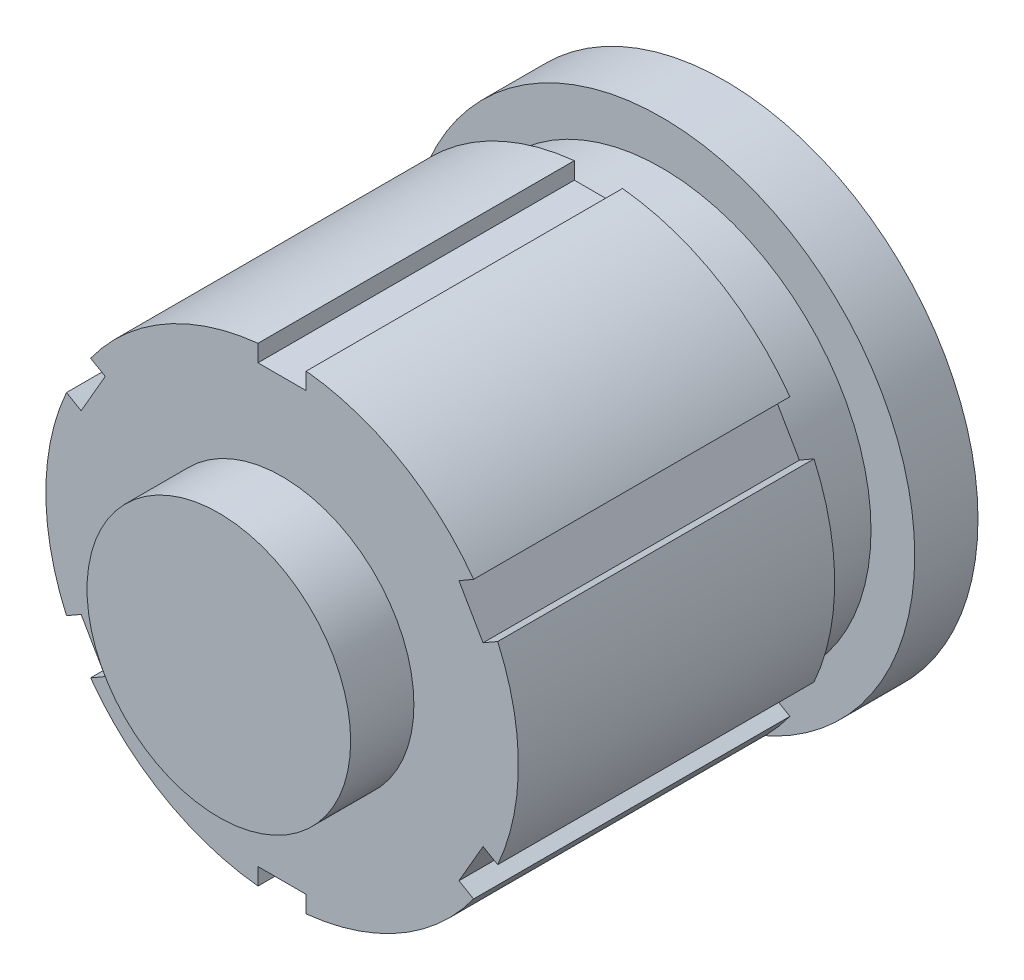
SolidWorks part; units mm, degrees
ref_plane "Alzado" through (0, 0, 0) normal (0, 0, 1) x (1, 0, 0)
ref_plane "Planta" through (0, 0, 0) normal (0, 1, 0) x (1, 0, 0)
ref_plane "Vista lateral" through (0, 0, 0) normal (1, 0, 0) x (0, 0, -1)
sketch "Croquis1" plane through (0, 0, 0) normal (0, 0, 1) x (1, 0, 0)
  circle A0 centre (0, 0) radius 20
  dimension "D1" = 40
extrude "Saliente-Extruir5" add sketch "Croquis1" along normal blind 5
sketch "Croquis6" plane through (0, 0, 5) normal (0, 0, 1) x (1, 0, 0)
  circle A0 centre (0, 0) radius 16.5443
extrude "Saliente-Extruir6" add sketch "Croquis6" along normal blind 5
sketch "Croquis7" plane through (0, 0, 10) normal (0, 0, 1) x (1, 0, 0)
  circle A0 centre (0, 0) radius 18.6737
extrude "Saliente-Extruir7" add sketch "Croquis7" along normal blind 25
sketch "Croquis8" plane through (0, 0, 35) normal (0, 0, 1) x (1, 0, 0)
  line L0 (16.4608, 11.7039) -> (15.883, 6.9698) construction
  line L1 (-1.9055, 20.1075) -> (1.9055, 20.1075)
  line L2 (-1.9055, 20.1075) -> (-1.9055, 17.24)
  line L3 (-1.9055, 17.24) -> (1.9055, 17.24)
  line L4 (1.9055, 20.1075) -> (1.9055, 17.24)
  line L5 (-1.9055, 20.1075) -> (1.9055, 17.24) construction
  line L6 (-1.9055, 17.24) -> (1.9055, 20.1075) construction
  line L7 (13.9776, 10.2702) -> (18.3663, 8.4035) construction
  line L8 (16.4608, 11.7039) -> (13.9776, 10.2702)
  line L9 (16.4608, 11.7039) -> (18.3663, 8.4035)
  line L10 (18.3663, 8.4035) -> (15.883, 6.9698)
  line L11 (13.9776, 10.2702) -> (15.883, 6.9698)
  line L12 (18.3663, -8.4035) -> (13.9776, -10.2702) construction
  line L13 (15.883, -6.9698) -> (16.4608, -11.7039) construction
  line L14 (18.3663, -8.4035) -> (15.883, -6.9698)
  line L15 (18.3663, -8.4035) -> (16.4608, -11.7039)
  line L16 (16.4608, -11.7039) -> (13.9776, -10.2702)
  line L17 (15.883, -6.9698) -> (13.9776, -10.2702)
  line L18 (1.9055, -20.1075) -> (-1.9055, -17.24) construction
  line L19 (1.9055, -17.24) -> (-1.9055, -20.1075) construction
  line L20 (1.9055, -20.1075) -> (1.9055, -17.24)
  line L21 (1.9055, -20.1075) -> (-1.9055, -20.1075)
  line L22 (-1.9055, -20.1075) -> (-1.9055, -17.24)
  line L23 (1.9055, -17.24) -> (-1.9055, -17.24)
  line L24 (-16.4608, -11.7039) -> (-15.883, -6.9698) construction
  line L25 (-13.9776, -10.2702) -> (-18.3663, -8.4035) construction
  line L26 (-16.4608, -11.7039) -> (-13.9776, -10.2702)
  line L27 (-16.4608, -11.7039) -> (-18.3663, -8.4035)
  line L28 (-18.3663, -8.4035) -> (-15.883, -6.9698)
  line L29 (-13.9776, -10.2702) -> (-15.883, -6.9698)
  line L30 (-18.3663, 8.4035) -> (-13.9776, 10.2702) construction
  line L31 (-15.883, 6.9698) -> (-16.4608, 11.7039) construction
  line L32 (-18.3663, 8.4035) -> (-15.883, 6.9698)
  line L33 (-18.3663, 8.4035) -> (-16.4608, 11.7039)
  line L34 (-16.4608, 11.7039) -> (-13.9776, 10.2702)
  line L35 (-15.883, 6.9698) -> (-13.9776, 10.2702)
  circle A0 centre (0, 0) radius 18.6737 construction
  point P0 (0, 18.6737)
  point P9 (16.1719, 9.3369)
  point P14 (16.1719, -9.3369)
  point P19 (0, -18.6737)
  point P24 (-16.1719, -9.3369)
  point P29 (-16.1719, 9.3369)
  point P34 (0, 0)
  dimension "D1" = 6
extrude "Cortar-Extruir2" cut sketch "Croquis8" against normal blind 25
sketch "Croquis9" plane through (0, 0, 35) normal (0, 0, 1) x (1, 0, 0)
  circle A0 centre (0, 0) radius 10.4174
extrude "Saliente-Extruir9" add sketch "Croquis9" along normal blind 5
